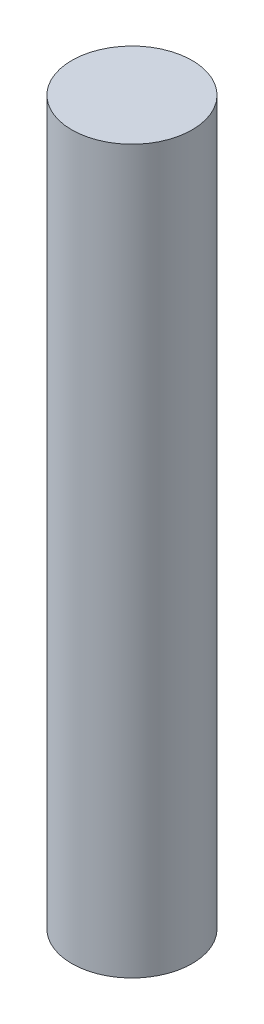
SolidWorks part; units mm, degrees
ref_plane "Front Plane" through (0, 0, 0) normal (0, 0, 1) x (1, 0, 0)
ref_plane "Top Plane" through (0, 0, 0) normal (0, 1, 0) x (1, 0, 0)
ref_plane "Right Plane" through (0, 0, 0) normal (1, 0, 0) x (0, 0, -1)
sketch "Sketch1" plane through (0, 0, 0) normal (0, 1, 0) x (1, 0, 0)
  circle A0 centre (0, 0) radius 2.5
extrude "Boss-Extrude1" add sketch "Sketch1" along normal blind 30
